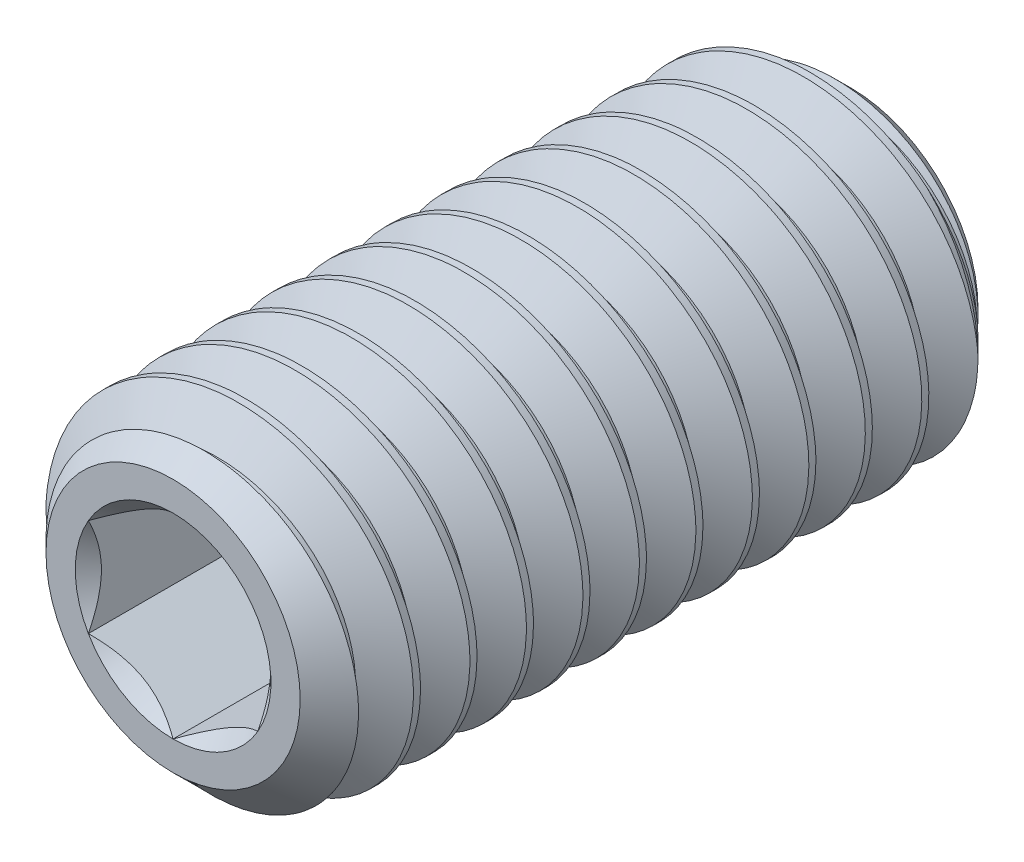
SolidWorks part; units mm, degrees
ref_plane "Front Plane" through (0, 0, 0) normal (0, 0, 1) x (1, 0, 0)
ref_plane "Top Plane" through (0, 0, 0) normal (0, 1, 0) x (1, 0, 0)
ref_plane "Right Plane" through (0, 0, 0) normal (1, 0, 0) x (0, 0, -1)
sketch "Sketch1" plane through (0, 0, 0) normal (1, 0, 0) x (0, 0, -1)
  line L0 (-3, 0) -> (3, 0) construction
  line L1 (-3, -1.5) -> (-3, 1.5) construction
  line L2 (-3, -0.75) -> (-3, 0.75) construction
  line L3 (-3, 1.5) -> (3, 1.5) construction
  line L4 (3, 1.5) -> (3, 0) construction
  line L5 (-3.4688, 1.5541) -> (-2.9688, 1.5541)
  line L6 (-2.9688, 1.5541) -> (-3.2188, 1.1211)
  line L7 (-3.2188, 1.1211) -> (-3.4688, 1.5541)
  line L8 (-3.2188, 1.1211) -> (-3.2188, 1.1752)
  line L9 (-3.2188, 1.5541) -> (-3.2188, 1.5)
  line L10 (-3.4375, 1.5) -> (-3, 1.5)
  line L11 (-3.4531, 1.5271) -> (-2.9844, 1.5271)
  line L12 (-3.25, 1.1752) -> (-3.1875, 1.1752)
  point P3 (-2.25, -1.5)
  point P4 (0, 0)
  point P8 (-3, 0)
  point P11 (-3, 0)
  point P21 (-3.2188, 1.5)
  point P24 (-3.2188, 1.5271)
  point P27 (-3.2188, 1.1752)
  dimension "Length" = 6
  dimension "Thread Size" = 3
  dimension "Drive Size" = 1.5
  dimension "Thread Pitch" = 0.5
  dimension "D1" = 0.0625
  dimension "D2" = 0.75
sketch "Sketch2" plane through (0, 0, 0) normal (1, 0, 0) x (0, 0, -1)
  line L1 (-3, 0) -> (3, 0)
  line L2 (-3, 0) -> (-3, 1.5)
  line L3 (-3, 1.5) -> (3, 1.5)
  line L4 (3, 0) -> (3, 1.5)
revolve "Revolve1" add sketch "Sketch2" angle 360 about L1
chamfer "Chamfer1" distance 0.375 angle 45 2 edges at (0, -1.5, -3) (0, -1.5, 3)
sketch "Sketch3" plane through (0, 0, 3) normal (0, 0, 1) x (1, 0, 0)
  line L0 (0, -0.75) -> (0, 0.75) construction
  line L1 (0, 0.866) -> (-0.75, 0.433)
  line L2 (-0.75, 0.433) -> (-0.75, -0.433)
  line L3 (-0.75, -0.433) -> (0, -0.866)
  line L4 (0, -0.866) -> (0.75, -0.433)
  line L5 (0.75, -0.433) -> (0.75, 0.433)
  line L6 (0.75, 0.433) -> (0, 0.866)
  line L7 (0, -1.5) -> (0, 1.5) construction
  circle A0 centre (0, 0) radius 0.75 construction
extrude "Cut-Extrude1" cut sketch "Sketch3" against normal blind 2.628
sketch "Sketch4" plane through (0, 0, 3) normal (0, 0, 1) x (1, 0, 0)
  line L0 (0, -1.5) -> (0, 1.5) construction
  circle A0 centre (0, 0) radius 0.866
extrude "Cut-Extrude2" cut sketch "Sketch4" against normal blind 2.628 draft 45
sketch "Sketch5" plane through (0, 0, 3) normal (0, 0, 1) x (1, 0, 0)
  line L0 (0, -1.5) -> (0, 1.5) construction
  circle A0 centre (0, 0) radius 1.5
curve "Helix/Spiral1" pitch 0.5 height 6.5 turns 13
sketch "Sketch6" plane through (0, 0, 0) normal (1, 0, 0) x (0, 0, -1)
  line L0 (-3.4531, 1.5271) -> (-2.9844, 1.5271)
  line L1 (-2.9844, 1.5271) -> (-3.1875, 1.1752)
  line L2 (-3.1875, 1.1752) -> (-3.25, 1.1752)
  line L3 (-3.25, 1.1752) -> (-3.4531, 1.5271)
sweep "Cut-Sweep1" cut profiles "Sketch6" path "Helix/Spiral1"
equation "\"D1@Sketch1\"=\"Thread Pitch@Sketch1\"/8"
equation "\"D1@Chamfer1\"=\"Thread Pitch@Sketch1\"*.75"
equation "\"D1@Cut-Extrude1\"=\"Length@Sketch1\"*.438"
equation "\"D1@Cut-Extrude2\"=\"D1@Cut-Extrude1\""
equation "\"D4@Helix/Spiral1\"=\"Thread Pitch@Sketch1\""
equation "\"D3@Helix/Spiral1\"=\"Thread Pitch@Sketch1\"+\"Length@Sketch1\""
equation "\"D2@Sketch1\"=\"Thread Pitch@Sketch1\"*1.5"
